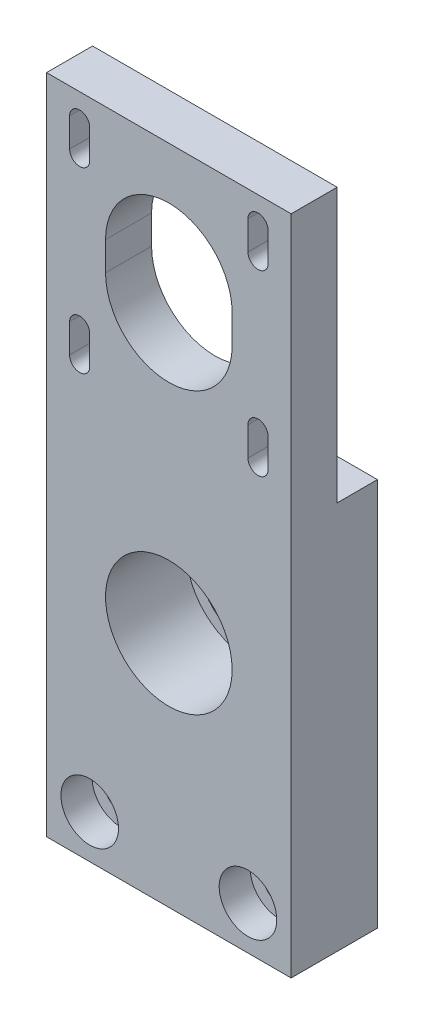
SolidWorks part; units mm, degrees
ref_plane "Ebene vorne" through (0, 0, 0) normal (0, 0, 1) x (1, 0, 0)
ref_plane "Ebene oben" through (0, 0, 0) normal (0, 1, 0) x (1, 0, 0)
ref_plane "Ebene rechts" through (0, 0, 0) normal (1, 0, 0) x (0, 0, -1)
sketch "Skizze1" plane through (0, 0, 0) normal (0, 0, 1) x (1, 0, 0)
  line L0 (21.25, 95) -> (21.25, 90) construction
  line L1 (0, 0) -> (42.5, 0)
  line L2 (0, 0) -> (0, 115)
  line L3 (0, 115) -> (42.5, 115)
  line L4 (42.5, 0) -> (42.5, 115)
  line L5 (32.25, 95) -> (32.25, 90)
  line L6 (10.25, 95) -> (10.25, 90)
  line L7 (5.75, 110.5) -> (5.75, 105.5) construction
  line L8 (7.5, 110.5) -> (7.5, 105.5)
  line L9 (4, 110.5) -> (4, 105.5)
  line L10 (36.75, 110.5) -> (36.75, 105.5) construction
  line L11 (38.5, 110.5) -> (38.5, 105.5)
  line L12 (35, 110.5) -> (35, 105.5)
  line L13 (36.75, 79.5) -> (36.75, 74.5) construction
  line L14 (38.5, 79.5) -> (38.5, 74.5)
  line L15 (35, 79.5) -> (35, 74.5)
  line L16 (5.75, 79.5) -> (5.75, 74.5) construction
  line L17 (7.5, 79.5) -> (7.5, 74.5)
  line L18 (4, 79.5) -> (4, 74.5)
  arc A0 (32.25, 95) -> (10.25, 95) centre (21.25, 95) ccw
  arc A1 (10.25, 90) -> (32.25, 90) centre (21.25, 90) ccw
  arc A2 (7.5, 110.5) -> (4, 110.5) centre (5.75, 110.5) ccw
  arc A3 (4, 105.5) -> (7.5, 105.5) centre (5.75, 105.5) ccw
  arc A4 (38.5, 110.5) -> (35, 110.5) centre (36.75, 110.5) ccw
  arc A5 (35, 105.5) -> (38.5, 105.5) centre (36.75, 105.5) ccw
  arc A6 (38.5, 79.5) -> (35, 79.5) centre (36.75, 79.5) ccw
  arc A7 (35, 74.5) -> (38.5, 74.5) centre (36.75, 74.5) ccw
  arc A8 (7.5, 79.5) -> (4, 79.5) centre (5.75, 79.5) ccw
  arc A9 (4, 74.5) -> (7.5, 74.5) centre (5.75, 74.5) ccw
  point P7 (21.25, 92.5)
  point P14 (5.75, 108)
  point P23 (36.75, 108)
  point P30 (36.75, 77)
  point P37 (5.75, 77)
  dimension "D1" = 42.5
  dimension "D2" = 115
  dimension "D3" = 5
  dimension "D4" = 22
  dimension "D5" = 21.25
  dimension "D6" = 22.5
  dimension "D7" = 3.5
  dimension "D8" = 5
  dimension "D9" = 15.5
  dimension "D10" = 15.5
  dimension "D11" = 2
  dimension "D12" = 2
extrude "Aufsatz-Linear austragen1" add sketch "Skizze1" along normal blind 15
sketch "Skizze2" plane through (0, 0, 15) normal (0, 0, 1) x (1, 0, 0)
  line L0 (0, 115) -> (0, 0) construction
  line L1 (16.819, 94.2796) -> (-0.905, 50.1478) construction
  line L2 (25.681, 94.2796) -> (43.405, 50.1478) construction
  circle A0 centre (21.25, 41.25) radius 11
  arc A1 (-0.905, 50.1478) -> (43.405, 50.1478) centre (21.25, 41.25) ccw construction
  arc A2 (25.681, 94.2796) -> (16.819, 94.2796) centre (21.25, 92.5) ccw construction
  dimension "D1" = 22
  dimension "D3" = 9.55
  dimension "D4" = 47.75
  dimension "D2" = 21.25
  dimension "D5" = 51.25
  dimension "D6" = 2.5
extrude "Schnitt-Linear austragen1" cut sketch "Skizze2" against normal blind 14
sketch "Skizze3" plane through (0, 0, 1) normal (0, 0, 1) x (1, 0, 0)
  circle A0 centre (21.25, 41.25) radius 9
  dimension "D1" = 18
extrude "Schnitt-Linear austragen2" cut sketch "Skizze3" against normal blind 14
sketch "Skizze4" plane through (0, 0, 15) normal (0, 0, 1) x (1, 0, 0)
  line L0 (42.5, 0) -> (42.5, 115) construction
  line L1 (0, 115) -> (0, 0) construction
  line L2 (0, 0) -> (42.5, 0) construction
  circle A0 centre (35, 7.5) radius 3.2736
  circle A1 centre (7.5, 7.5) radius 3.7619
  dimension "D1" = 7.5
  dimension "D2" = 7.5
  dimension "D3" = 7.5
hole_wizard "Stirnsenkung für M5 Zylinderschraube mit Innensechskant1" positions "3D-Skizze1" profile "Skizze5" counterbore size "M5" standard "DIN" end condition through all
sketch3d "3D-Skizze1"
  point P0 (35, 7.5, 15)
  point P3 (7.5, 7.5, 15)
sketch "Skizze5" plane through (35, 7.5, 15) normal (1, 0, 0) x (0, -1, 0)
  line L0 (0, 0) -> (0, 15)
  line L1 (0, 15) -> (2.75, 15)
  line L3 (2.75, 15) -> (2.75, 5.4)
  line L4 (2.75, 5.4) -> (5, 5.4)
  line L5 (5, 5.4) -> (5, 0)
  line L7 (5, 0) -> (0, 0)
  line L11 (0, -6.35) -> (0, 107.95) construction
  dimension "Bohrerdurchmesser" = 5.5
  dimension "Bohrungstiefe" = 15
  dimension "Senkdurchmesser2" = 10
  dimension "Senktiefe2" = 5.4
sketch "Skizze6" plane through (42.5, 0, 0) normal (1, 0, 0) x (0, 0, -1)
  line L0 (0, 0) -> (0, 115) construction
  line L1 (0, 67.5) -> (-7, 67.5)
  line L2 (0, 67.5) -> (0, 115)
  line L3 (0, 115) -> (-7, 115)
  line L4 (-7, 67.5) -> (-7, 115)
  line L6 (-15, 115) -> (0, 115) construction
  line L7 (-15, 90) -> (0, 90) construction
  dimension "D1" = 7
  dimension "D2" = 22.5
extrude "Schnitt-Linear austragen3" cut sketch "Skizze6" against normal blind 50
